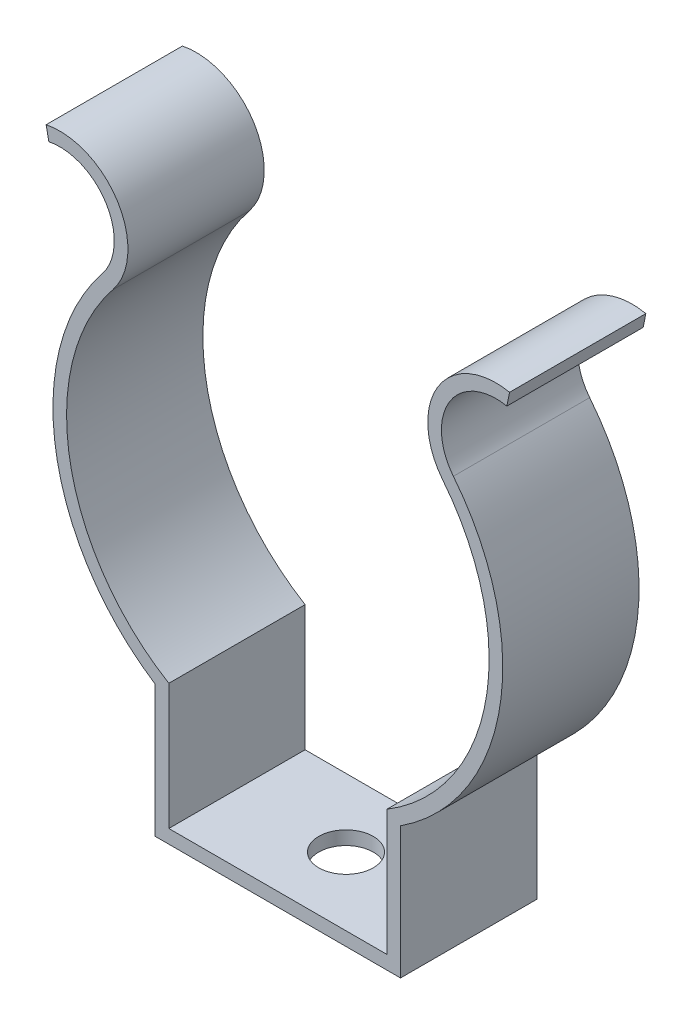
SolidWorks part; units mm, degrees
ref_plane "Front Plane" through (0, 0, 0) normal (0, 0, 1) x (1, 0, 0)
ref_plane "Top Plane" through (0, 0, 0) normal (0, 1, 0) x (1, 0, 0)
ref_plane "Right Plane" through (0, 0, 0) normal (1, 0, 0) x (0, 0, -1)
sketch "Sketch1" plane through (0, 0, 0) normal (0, 0, 1) x (1, 0, 0)
  line L0 (0, -15.5) -> (9.7399, -15.5) construction
  line L1 (8, -15.5) -> (8, -22.5) construction
  line L2 (8, -22.5) -> (-8, -22.5) construction
  line L3 (-8, -22.5) -> (-8, -13.2759) construction
  line L4 (0, 0) -> (0, -15.5) construction
  line L5 (8, -22.5) -> (8, -13.2759)
  line L6 (-8, -13.2759) -> (-8, -22.5)
  line L7 (-8, -22.5) -> (8, -22.5)
  line L8 (11, 12.816) -> (11, 4.5034) construction
  line L9 (-11, 12.816) -> (-11, 4.5034) construction
  line L10 (9, -23.5) -> (9, -13.8293)
  line L11 (-9, -23.5) -> (9, -23.5)
  line L12 (-9, -13.8293) -> (-9, -23.5)
  line L13 (-17, 17.715) -> (-16.8, 16.7352)
  line L14 (17, 17.715) -> (16.8, 16.7352)
  circle A0 centre (0, 0) radius 15.5 construction
  arc A1 (-8, -13.2759) -> (-12.0976, 9.6902) centre (0, 0) cw
  arc A2 (8, -13.2759) -> (12.0976, 9.6902) centre (0, 0) ccw
  arc A3 (-12.0976, 9.6902) -> (-17, 17.715) centre (-16, 12.816) ccw
  arc A4 (12.0976, 9.6902) -> (17, 17.715) centre (16, 12.816) cw
  arc A5 (12.878, 10.3153) -> (16.8, 16.7352) centre (16, 12.816) cw
  arc A6 (9, -13.8293) -> (12.878, 10.3153) centre (0, 0) ccw
  arc A7 (-9, -13.8293) -> (-12.878, 10.3153) centre (0, 0) cw
  arc A8 (-12.878, 10.3153) -> (-16.8, 16.7352) centre (-16, 12.816) ccw
  dimension "D1" = 31
  dimension "D4" = 5
  dimension "D2" = 8
  dimension "D3" = 16
  dimension "D5" = 22
  dimension "D6" = 34
  dimension "D7" = 1
extrude "Boss-Extrude1" add sketch "Sketch1" along normal blind 10
sketch "Sketch2" plane through (0, -22.5, 0) normal (0, 1, 0) x (1, 0, 0)
  line L0 (0, 0) -> (0, -10) construction
  line L1 (8, 0) -> (-8, 0) construction
  line L2 (8, -10) -> (-8, -10) construction
  circle A0 centre (0, -5) radius 2
  dimension "D1" = 4
extrude "Cut-Extrude1" cut sketch "Sketch2" against normal blind 10
